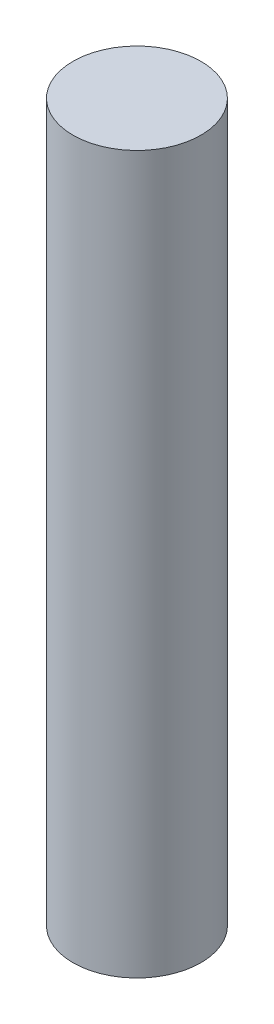
SolidWorks part; units mm, degrees
ref_plane "Front Plane" through (0, 0, 0) normal (0, 0, 1) x (1, 0, 0)
ref_plane "Top Plane" through (0, 0, 0) normal (0, 1, 0) x (1, 0, 0)
ref_plane "Right Plane" through (0, 0, 0) normal (1, 0, 0) x (0, 0, -1)
sketch "Sketch1" plane through (0, 0, 0) normal (0, 1, 0) x (1, 0, 0)
  circle A0 centre (0, 0) radius 1.5875
  dimension "D1" = 3.175
extrude "Boss-Extrude1" add sketch "Sketch1" along normal blind 17.78
